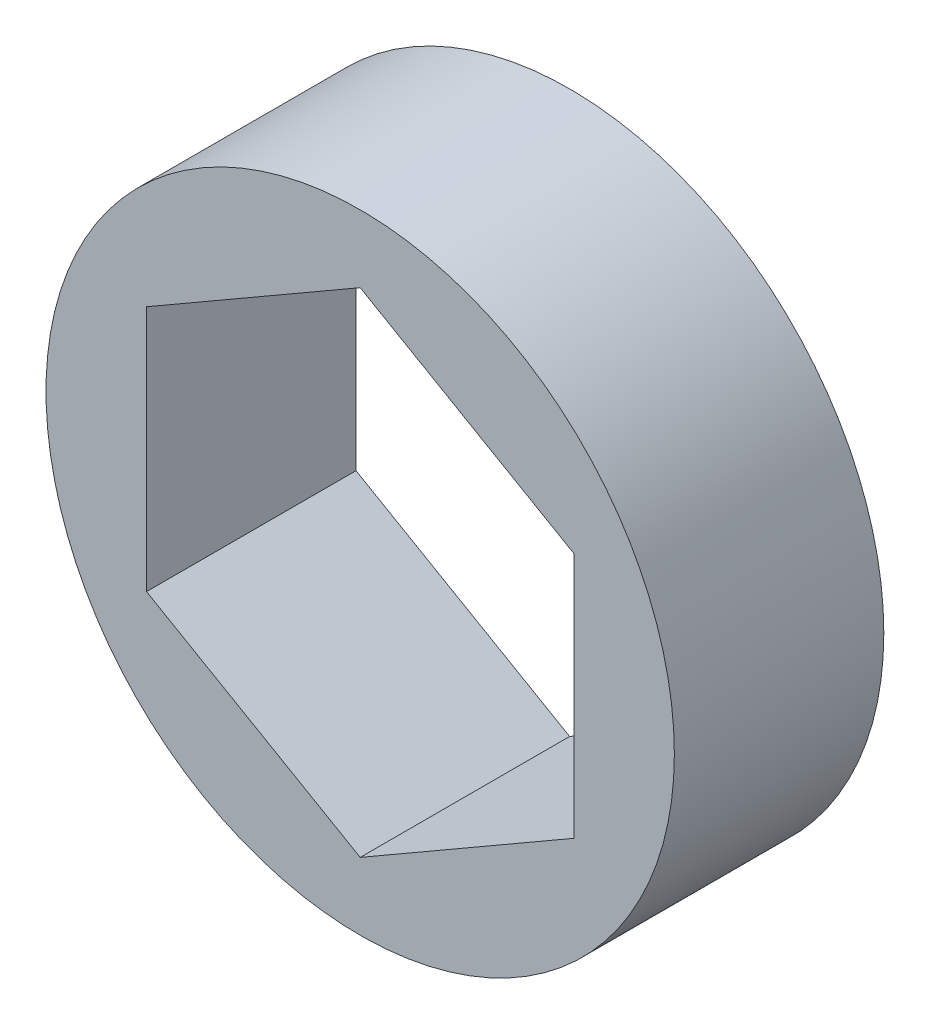
SolidWorks part; units mm, degrees
material "PET"
ref_plane "Front Plane" through (0, 0, 0) normal (0, 0, 1) x (1, 0, 0)
ref_plane "Top Plane" through (0, 0, 0) normal (0, 1, 0) x (1, 0, 0)
ref_plane "Right Plane" through (0, 0, 0) normal (1, 0, 0) x (0, 0, -1)
sketch "Sketch1" plane through (0, 0, 0) normal (0, 0, 1) x (1, 0, 0)
  line L1 (0, 7.479) -> (-6.477, 3.7395)
  line L2 (-6.477, 3.7395) -> (-6.477, -3.7395)
  line L3 (-6.477, -3.7395) -> (0, -7.479)
  line L4 (0, -7.479) -> (6.477, -3.7395)
  line L5 (6.477, -3.7395) -> (6.477, 3.7395)
  line L6 (6.477, 3.7395) -> (0, 7.479)
  circle A0 centre (0, 0) radius 6.477 construction
  circle A1 centre (0, 0) radius 9.525
  dimension "D1" = 12.954
  dimension "D2" = 19.05
extrude "Boss-Extrude1" add sketch "Sketch1" along normal mid plane 6.35
